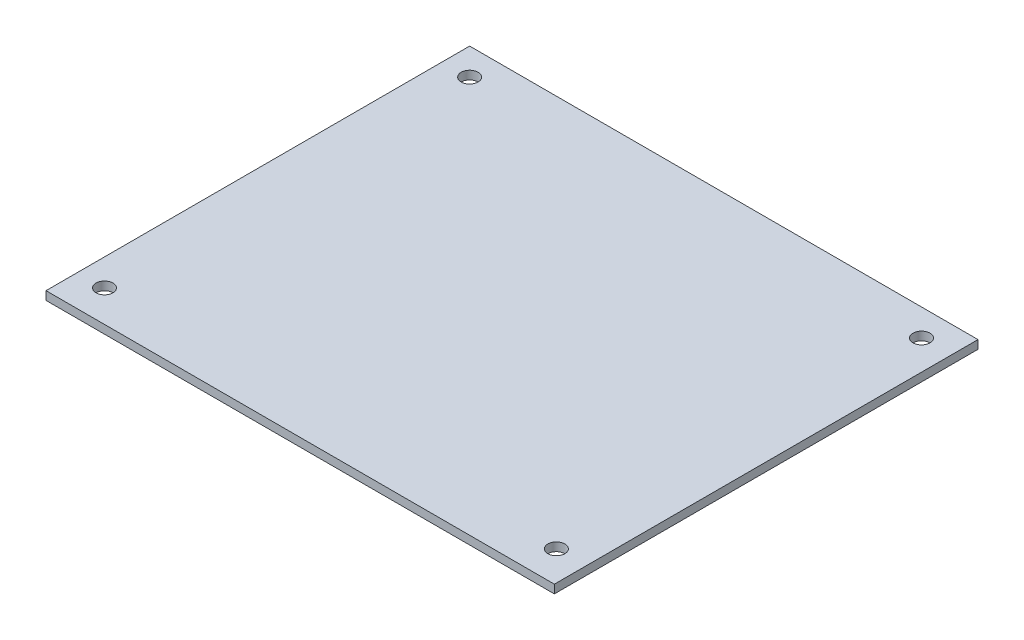
SolidWorks part; units mm, degrees
ref_plane "Front Plane" through (0, 0, 0) normal (0, 0, 1) x (1, 0, 0)
ref_plane "Top Plane" through (0, 0, 0) normal (0, 1, 0) x (1, 0, 0)
ref_plane "Right Plane" through (0, 0, 0) normal (1, 0, 0) x (0, 0, -1)
sketch "Sketch1" plane through (0, 0, 0) normal (0, 1, 0) x (1, 0, 0)
  line L1 (0, 0) -> (96, 0)
  line L2 (0, 0) -> (0, 80)
  line L3 (0, 80) -> (96, 80)
  line L4 (96, 0) -> (96, 80)
  circle A0 centre (5.08, 74.92) radius 1.6
  circle A1 centre (90.412, 74.92) radius 1.6
  circle A2 centre (90.412, 5.969) radius 1.6
  circle A3 centre (5.08, 5.969) radius 1.6
  dimension "D3" = 3.2
  dimension "D1" = 96
  dimension "D2" = 80
  dimension "D4" = 5.08
  dimension "D5" = 5.08
  dimension "D6" = 5.969
  dimension "D7" = 5.588
extrude "Boss-Extrude1" add sketch "Sketch1" along normal blind 1.6 contours L3 L4 L1 L2
sketch "Sketch2" plane through (0, 1.6, 0) normal (0, 1, 0) x (1, 0, 0)
  line L0 (96, 80) -> (0, 80) construction
  line L1 (96, 0) -> (96, 80) construction
  point P0 (80.252, 74.92)
  point P1 (52.566, 74.92)
  point P2 (39.993, 64.506)
  dimension "D1" = 5.08
  dimension "D2" = 15.748
  dimension "D3" = 27.686
  dimension "D4" = 12.573
  dimension "D5" = 10.414
